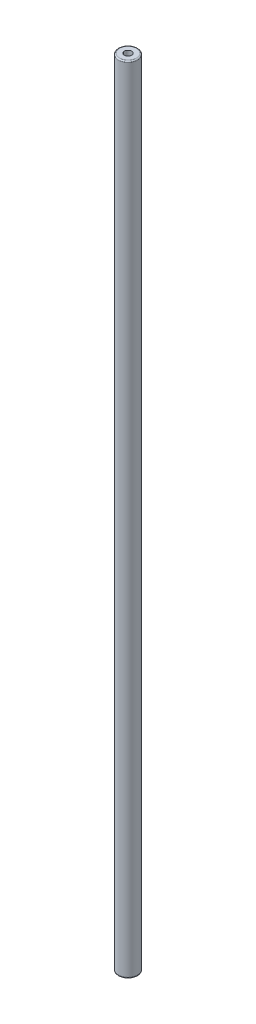
SolidWorks part; units mm, degrees
ref_plane "Спереди" through (0, 0, 0) normal (0, 0, 1) x (1, 0, 0)
ref_plane "Сверху" through (0, 0, 0) normal (0, 1, 0) x (1, 0, 0)
ref_plane "Справа" through (0, 0, 0) normal (1, 0, 0) x (0, 0, -1)
ref_plane "Плоскость1"
sketch "Эскиз1" plane through (0, 0, 0) normal (0, 1, 0) x (-1, 0, 0)
  circle A0 centre (0, 0) radius 4
  dimension "D1" = 8
extrude "Выдавливание1" add sketch "Эскиз1" along normal blind 164.95 and the other way blind 164.95
sketch "Эскиз2" plane through (0, 164.95, 0) normal (0, 1, 0) x (-1, 0, 0)
  circle A0 centre (0, 0) radius 1.5
  dimension "D1" = 3
extrude "Выдавливание2" cut sketch "Эскиз2" against normal blind 5
ref_plane "Плоскость2" through (0, 0, 0) normal (0, 1, 0) x (-1, 0, 0)
mirror "Зеркальное отражение1" about plane through (0, 0, 0) normal (0, 1, 0) of "Выдавливание2"
fillet "Сопряжение1" radius 0.5 2 edges at (0, 164.95, 4) (0, -164.95, 4)
